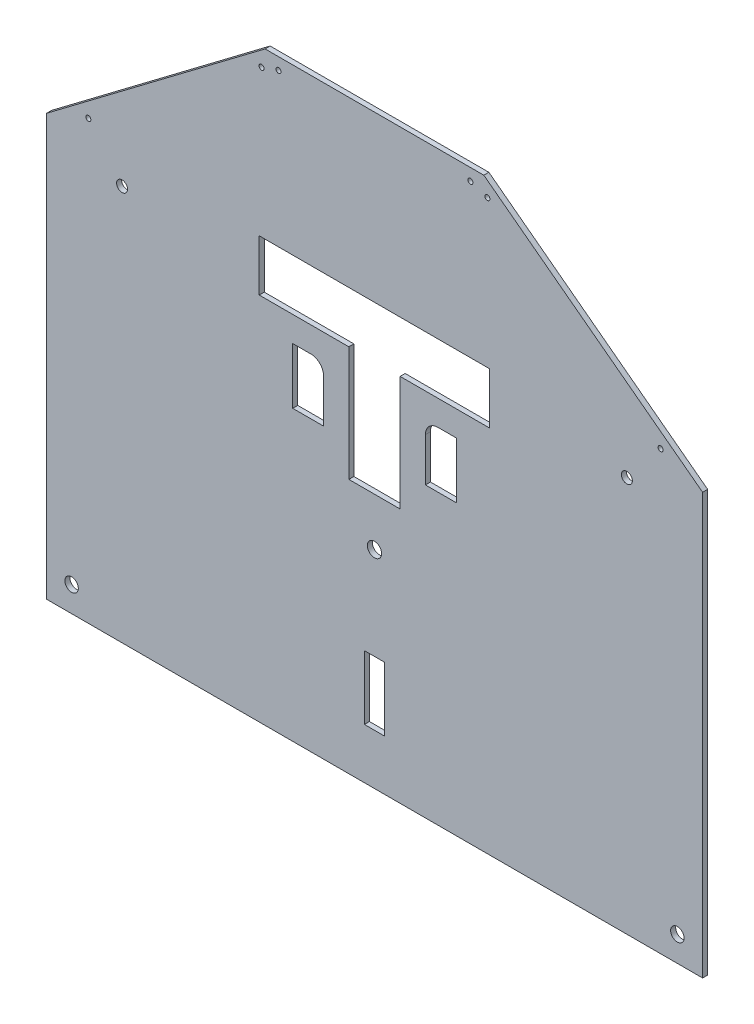
SolidWorks part; units mm, degrees
ref_plane "Front Plane" through (0, 0, 0) normal (0, 0, 1) x (1, 0, 0)
ref_plane "Top Plane" through (0, 0, 0) normal (0, 1, 0) x (1, 0, 0)
ref_plane "Right Plane" through (0, 0, 0) normal (1, 0, 0) x (0, 0, -1)
sketch "Sketch1" plane through (0, 0, 0) normal (0, 0, 1) x (1, 0, 0)
  line L0 (0, 0) -> (403.39, 0)
  line L1 (403.39, 0) -> (403.39, 241)
  line L2 (403.39, 241) -> (274.41, 359.5)
  line L3 (274.41, 359.5) -> (128.98, 359.5)
  line L4 (128.98, 359.5) -> (0, 241)
  line L5 (0, 241) -> (0, 0)
  line L6 (201.695, 359.5) -> (201.695, 0) construction
  line L7 (216.695, 223) -> (246.695, 223)
  line L8 (156.695, 223) -> (186.695, 223)
  line L9 (156.695, 223) -> (156.695, 253)
  line L10 (156.695, 253) -> (246.695, 253)
  line L11 (246.695, 223) -> (246.695, 253)
  line L13 (186.695, 223) -> (186.695, 219.825)
  line L14 (186.695, 219.825) -> (216.695, 219.825)
  line L15 (216.695, 223) -> (216.695, 219.825)
  dimension "D1" = 403.39
  dimension "D2" = 241
  dimension "D3" = 359.5
  dimension "D4" = 145.43
  dimension "D5" = 30
  dimension "D6" = 90
  dimension "D7" = 223
  dimension "D8" = 45
  dimension "D9" = 3.175
  dimension "D10" = 30
  dimension "D11" = 15
extrude "Boss-Extrude1" add sketch "Sketch1" along normal blind 3
sketch "Croquis1" plane through (0, 0, 3) normal (0, 0, 1) x (1, 0, 0)
  line L1 (0, 0) -> (403.39, 0) construction
  line L2 (6.695, 0) -> (-43.8803, 0)
  line L3 (396.695, 0) -> (517.7066, 0)
  line L4 (396.695, 0) -> (396.695, 356.3167)
  line L5 (396.695, 356.3167) -> (517.7066, 356.3167)
  line L6 (517.7066, 0) -> (517.7066, 356.3167)
  line L7 (6.695, 0) -> (6.695, 364.8833)
  line L8 (6.695, 364.8833) -> (-43.8803, 364.8833)
  line L9 (-43.8803, 0) -> (-43.8803, 364.8833)
  point P10 (201.695, 0)
  dimension "D1" = 195
extrude "Cortar-Extruir1" cut sketch "Croquis1" against normal blind 10
sketch "Croquis2" plane through (0, 0, 3) normal (0, 0, 1) x (1, 0, 0)
  line L0 (396.695, 247.151) -> (396.695, 0) construction
  line L1 (6.695, 0) -> (396.695, 0)
  line L2 (6.695, 0) -> (6.695, 250)
  line L3 (6.695, 250) -> (396.695, 250)
  line L4 (396.695, 0) -> (396.695, 250)
  dimension "D1" = 250
extrude "Saliente-Extruir1" add sketch "Croquis2" against normal blind 3
sketch "Croquis3" plane through (0, 0, 3) normal (0, 0, 1) x (1, 0, 0)
  line L0 (9.7959, 250) -> (6.695, 250) construction
  line L1 (171.695, 220) -> (231.695, 220)
  line L2 (171.695, 220) -> (171.695, 250)
  line L3 (171.695, 250) -> (231.695, 250)
  line L4 (231.695, 220) -> (231.695, 250)
  line L5 (396.695, 250) -> (396.695, 0) construction
  point P6 (201.695, 220)
  dimension "D1" = 0
  dimension "D2" = 195
  dimension "D3" = 60
  dimension "D4" = 30
extrude "Cortar-Extruir3" cut sketch "Croquis3" against normal blind 3
sketch "Croquis4" plane through (0, 0, 3) normal (0, 0, 1) x (1, 0, 0)
  line L1 (156.695, 250) -> (246.695, 250)
  line L2 (156.695, 250) -> (156.695, 253)
  line L3 (156.695, 253) -> (246.695, 253)
  line L4 (246.695, 250) -> (246.695, 253)
extrude "Saliente-Extruir2" add sketch "Croquis4" against normal blind 3
sketch "Croquis5" plane through (0, 0, 3) normal (0, 0, 1) x (1, 0, 0)
  line L0 (171.695, 220) -> (231.695, 220) construction
  line L1 (186.695, 220) -> (216.695, 220)
  line L2 (186.695, 220) -> (186.695, 190)
  line L3 (186.695, 190) -> (216.695, 190)
  line L4 (216.695, 220) -> (216.695, 190)
  dimension "D1" = 15
  dimension "D2" = 30
extrude "Cortar-Extruir4" cut sketch "Croquis5" against normal blind 3
sketch "Croquis6" plane through (0, 0, 3) normal (0, 0, 1) x (1, 0, 0)
  line L1 (186.695, 190) -> (216.695, 190)
  line L2 (186.695, 190) -> (186.695, 151.5)
  line L3 (186.695, 151.5) -> (216.695, 151.5)
  line L4 (216.695, 190) -> (216.695, 151.5)
extrude "Cortar-Extruir5" cut sketch "Croquis6" against normal blind 3
sketch "Croquis7" plane through (0, 0, 3) normal (0, 0, 1) x (1, 0, 0)
  line L1 (171.695, 220) -> (133.195, 220)
  line L2 (171.695, 220) -> (171.695, 250)
  line L3 (171.695, 250) -> (133.195, 250)
  line L4 (133.195, 220) -> (133.195, 250)
  line L5 (231.695, 220) -> (270.195, 220)
  line L6 (231.695, 220) -> (231.695, 250)
  line L7 (231.695, 250) -> (270.195, 250)
  line L8 (270.195, 220) -> (270.195, 250)
extrude "Cortar-Extruir6" cut sketch "Croquis7" against normal blind 3
sketch "Croquis8" plane through (0, 0, 3) normal (0, 0, 1) x (1, 0, 0)
  line L0 (270.195, 220) -> (270.195, 250) construction
  line L1 (133.195, 250) -> (270.195, 250)
  line L2 (133.195, 250) -> (133.195, 250.25)
  line L3 (133.195, 250.25) -> (270.195, 250.25)
  line L4 (270.195, 250) -> (270.195, 250.25)
  line L6 (133.195, 220) -> (270.195, 220)
  line L7 (133.195, 220) -> (133.195, 219.75)
  line L8 (133.195, 219.75) -> (270.195, 219.75)
  line L9 (270.195, 220) -> (270.195, 219.75)
extrude "Cortar-Extruir7" cut sketch "Croquis8" against normal blind 3
sketch "Croquis9" plane through (0, 0, 3) normal (0, 0, 1) x (1, 0, 0)
  line L1 (186.695, 151.5) -> (186.445, 151.5)
  line L2 (186.695, 151.5) -> (186.695, 219.75)
  line L3 (186.695, 219.75) -> (186.445, 219.75)
  line L4 (186.445, 151.5) -> (186.445, 219.75)
  line L9 (216.695, 151.5) -> (216.945, 151.5)
  line L10 (216.695, 151.5) -> (216.695, 219.75)
  line L11 (216.695, 219.75) -> (216.945, 219.75)
  line L12 (216.945, 151.5) -> (216.945, 219.75)
extrude "Cortar-Extruir8" cut sketch "Croquis9" against normal blind 3
sketch "Croquis10" plane through (0, 0, 3) normal (0, 0, 1) x (1, 0, 0)
  line L0 (136.695, 348.1652) -> (266.695, 348.1652)
  line L1 (396.695, 250) -> (266.695, 348.1652)
  line L2 (6.695, 250) -> (136.695, 348.1652)
  line L3 (396.695, 250) -> (396.695, 0) construction
  line L4 (6.695, 250) -> (24.2519, 412.1179)
  line L5 (24.2519, 412.1179) -> (402.243, 389.3081)
  line L6 (402.243, 389.3081) -> (396.695, 250)
  point P5 (201.695, 348.1652)
  dimension "D1" = 130
  dimension "D2" = 195
  dimension "D3" = 162.9
extrude "Cortar-Extruir9" cut sketch "Croquis10" against normal blind 3
sketch "Croquis11" plane through (0, 0, 3) normal (0, 0, 1) x (1, 0, 0)
  line L0 (51.7331, 284.009) -> (6.695, 250)
  line L1 (24.1062, 263.1475) -> (136.695, 348.1652) construction
  line L2 (6.695, 250) -> (31.6504, 216.9517)
  line L3 (31.6504, 216.9517) -> (51.7331, 284.009)
  line L4 (347.8891, 286.8542) -> (396.695, 250)
  line L5 (266.695, 348.1652) -> (379.2838, 263.1475) construction
  line L6 (396.695, 250) -> (356.6234, 225.7292)
  line L7 (356.6234, 225.7292) -> (347.8891, 286.8542)
extrude "Saliente-Extruir3" add sketch "Croquis11" against normal blind 3
sketch "Croquis12" plane through (0, 0, 3) normal (0, 0, 1) x (1, 0, 0)
  line L0 (6.695, 0) -> (6.695, 250) construction
  line L1 (6.695, 0) -> (396.695, 0) construction
  line L2 (396.695, 250) -> (396.695, 0) construction
  circle A0 centre (21.695, 15) radius 4
  circle A1 centre (381.695, 15) radius 4
  circle A2 centre (51.695, 235) radius 4
  circle A3 centre (351.695, 235) radius 4
  dimension "D1" = 15
  dimension "D3" = 15
  dimension "D4" = 15
  dimension "D5" = 8
  dimension "D6" = 45
  dimension "D2" = 15
  dimension "D7" = 15
  dimension "D8" = 45
extrude "Cortar-Extruir10" cut sketch "Croquis12" against normal blind 3
sketch "Croquis13" plane through (0, 0, 3) normal (0, 0, 1) x (1, 0, 0)
  circle A0 centre (51.695, 235) radius 3.25
  circle A1 centre (51.695, 235) radius 4.25
  circle A2 centre (351.695, 235) radius 3.25
  circle A3 centre (351.695, 235) radius 4.25
extrude "Saliente-Extruir4" add sketch "Croquis13" against normal blind 3
sketch "Croquis14" plane through (0, 0, 3) normal (0, 0, 1) x (1, 0, 0)
  line L0 (6.695, 0) -> (396.695, 0) construction
  line L1 (396.695, 250) -> (396.695, 0) construction
  circle A0 centre (201.695, 35) radius 4.25
  circle A1 centre (201.695, 123) radius 4.25
  dimension "D1" = 35
  dimension "D2" = 8.5
  dimension "D3" = 195
  dimension "D4" = 88
extrude "Cortar-Extruir11" cut sketch "Croquis14" against normal blind 3
sketch "Croquis15" plane through (0, 0, 3) normal (0, 0, 1) x (1, 0, 0)
  circle A0 centre (201.695, 38) radius 4.25
  circle A1 centre (201.695, 35) radius 4.25 construction
  dimension "D1" = 3
extrude "Cortar-Extruir12" cut sketch "Croquis15" against normal blind 25
sketch "Croquis16" plane through (0, 0, 3) normal (0, 0, 1) x (1, 0, 0)
  circle A0 centre (201.695, 38) radius 4.25
  circle A1 centre (201.695, 35) radius 4.25
  arc M2 (205.6715, 36.5) -> (197.7185, 36.5) centre (201.695, 35) cw
extrude "Saliente-Extruir5" add sketch "Croquis16" against normal blind 3 contours A0 M2
sketch "Croquis17" plane through (0, 0, 3) normal (0, 0, 1) x (1, 0, 0)
  line L0 (136.695, 348.1652) -> (266.695, 348.1652) construction
  line L1 (6.695, 250) -> (136.695, 348.1652) construction
  line L2 (266.695, 348.1652) -> (396.695, 250) construction
  line L3 (266.695, 348.1652) -> (262.4165, 342.4992) construction
  line L4 (262.4165, 342.4992) -> (268.8008, 337.6783) construction
  circle A0 centre (146.5687, 341.0652) radius 1.5
  circle A1 centre (254.9773, 341.0652) radius 1.5
  circle A2 centre (134.5892, 337.6783) radius 1.5
  circle A3 centre (31.6427, 259.9416) radius 1.5
  circle A4 centre (268.8008, 337.6783) radius 1.5
  circle A5 centre (371.7473, 259.9416) radius 1.5
  dimension "D1" = 7.1
  dimension "D2" = 7.1
  dimension "D3" = 7.1
  dimension "D4" = 7.1
  dimension "D5" = 7.1
  dimension "D6" = 7.1
  dimension "D7" = 129
  dimension "D8" = 129
  dimension "D9" = 90
  dimension "D10" = 90
  dimension "D11" = 8
  dimension "D12" = 0
extrude "Cortar-Extruir13" cut sketch "Croquis17" against normal blind 10
sketch "Croquis18" plane through (0, 0, 3) normal (0, 0, 1) x (1, 0, 0)
  line L0 (136.695, 348.1652) -> (266.695, 348.1652) construction
  circle A0 centre (144.695, 341.0652) radius 1.5
  circle A1 centre (258.695, 341.0652) radius 1.5
  dimension "D1" = 7.1
  dimension "D2" = 8
  dimension "D3" = 8
extrude "Cortar-Extruir14" cut sketch "Croquis18" against normal blind 30
sketch "Croquis19" plane through (0, 0, 3) normal (0, 0, 1) x (1, 0, 0)
  circle A0 centre (254.9773, 341.0652) radius 1.5
  circle A1 centre (146.5687, 341.0652) radius 1.5
  circle A2 centre (144.695, 341.0652) radius 1.5
  arc M1 (145.6319, 339.8938) -> (145.6319, 342.2367) centre (144.695, 341.0652) cw
  circle M5 centre (254.9773, 341.0652) radius 1.5
extrude "Saliente-Extruir6" add sketch "Croquis19" against normal blind 3 contours A1 M1 | M5
sketch "Croquis21" plane through (0, 0, 3) normal (0, 0, 1) x (1, 0, 0)
  line L0 (136.695, 348.1652) -> (266.695, 348.1652) construction
  circle A0 centre (144.695, 341.0652) radius 1.5
  dimension "D1" = 7.1
  dimension "D2" = 8
extrude "Cortar-Extruir15" cut sketch "Croquis21" against normal blind 3
sketch "Croquis22" plane through (0, 0, 3) normal (0, 0, 1) x (1, 0, 0)
  circle A0 centre (144.695, 341.0652) radius 1.5
  circle A1 centre (146.5687, 341.0652) radius 1.5
  arc M2 (145.6319, 342.2367) -> (145.6319, 339.8938) centre (146.5687, 341.0652) cw
extrude "Saliente-Extruir7" add sketch "Croquis22" against normal blind 3 contours A0 M2
sketch "Croquis23" plane through (0, 0, 3) normal (0, 0, 1) x (1, 0, 0)
  line L0 (216.945, 219.75) -> (250.295, 219.75) construction
  line L1 (216.945, 219.75) -> (270.195, 219.75) construction
  line L2 (250.295, 219.75) -> (250.295, 204.75) construction
  line L3 (250.295, 204.75) -> (239.445, 204.75)
  line L4 (239.445, 204.75) -> (239.445, 197.25) construction
  line L5 (239.445, 197.25) -> (231.945, 197.25) construction
  line L6 (231.945, 197.25) -> (231.945, 171.4)
  line L7 (231.945, 171.4) -> (250.295, 171.4)
  line L8 (250.295, 171.4) -> (250.295, 204.75)
  line L9 (186.445, 219.75) -> (153.095, 219.75) construction
  line L10 (133.195, 219.75) -> (186.445, 219.75) construction
  line L11 (153.095, 219.75) -> (153.095, 204.75) construction
  line L12 (153.095, 204.75) -> (163.945, 204.75)
  line L13 (163.945, 204.75) -> (163.945, 197.25) construction
  line L14 (163.945, 197.25) -> (171.445, 197.25) construction
  line L15 (171.445, 197.25) -> (171.445, 171.4)
  line L16 (171.445, 171.4) -> (153.095, 171.4)
  line L17 (153.095, 171.4) -> (153.095, 204.75)
  arc A0 (239.445, 204.75) -> (231.945, 197.25) centre (239.445, 197.25) ccw
  arc A1 (163.945, 204.75) -> (171.445, 197.25) centre (163.945, 197.25) cw
  dimension "D1" = 15
extrude "Cortar-Extruir17" cut sketch "Croquis23" against normal blind 10 contours A1 L12 L17 L16 L15 | L3 A0 L6 L7 L8
sketch "Croquis25" plane through (0, 0, 3) normal (0, 0, 1) x (1, 0, 0)
  line L0 (195.695, 38) -> (195.695, 30)
  line L1 (195.695, 30) -> (207.695, 30)
  line L2 (207.695, 30) -> (207.695, 38)
  line L3 (6.695, 0) -> (396.695, 0) construction
  line L4 (195.695, 38) -> (195.695, 68)
  line L5 (195.695, 68) -> (207.695, 68)
  line L6 (207.695, 68) -> (207.695, 38)
  dimension "D1" = 30
extrude "Cortar-Extruir18" cut sketch "Croquis25" against normal blind 10
